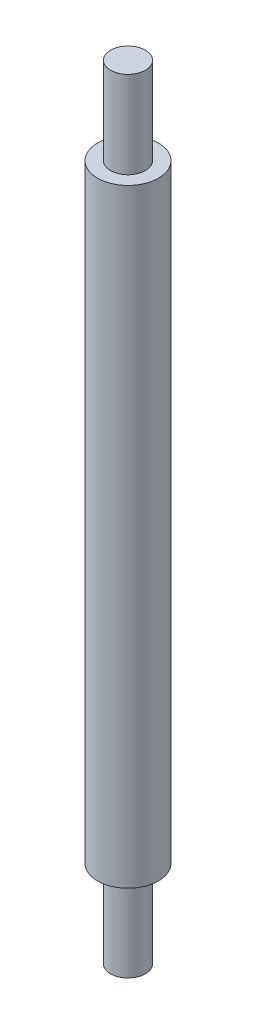
SolidWorks part; units mm, degrees
ref_plane "Front Plane" through (0, 0, 0) normal (0, 0, 1) x (1, 0, 0)
ref_plane "Top Plane" through (0, 0, 0) normal (0, 1, 0) x (1, 0, 0)
ref_plane "Right Plane" through (0, 0, 0) normal (1, 0, 0) x (0, 0, -1)
sketch "Sketch1" plane through (0, 0, 0) normal (0, 1, 0) x (1, 0, 0)
  circle A0 centre (0, 0) radius 3.5
extrude "Boss-Extrude1" add sketch "Sketch1" along normal blind 70
sketch "Sketch2" plane through (0, 70, 0) normal (0, 1, 0) x (1, 0, 0)
  circle A0 centre (0, 0) radius 2
extrude "Boss-Extrude2" add sketch "Sketch2" along normal blind 10
sketch "Sketch3" plane through (0, 0, 0) normal (0, -1, 0) x (1, 0, 0)
  circle A0 centre (0, 0) radius 2
extrude "Boss-Extrude3" add sketch "Sketch3" along normal blind 10
